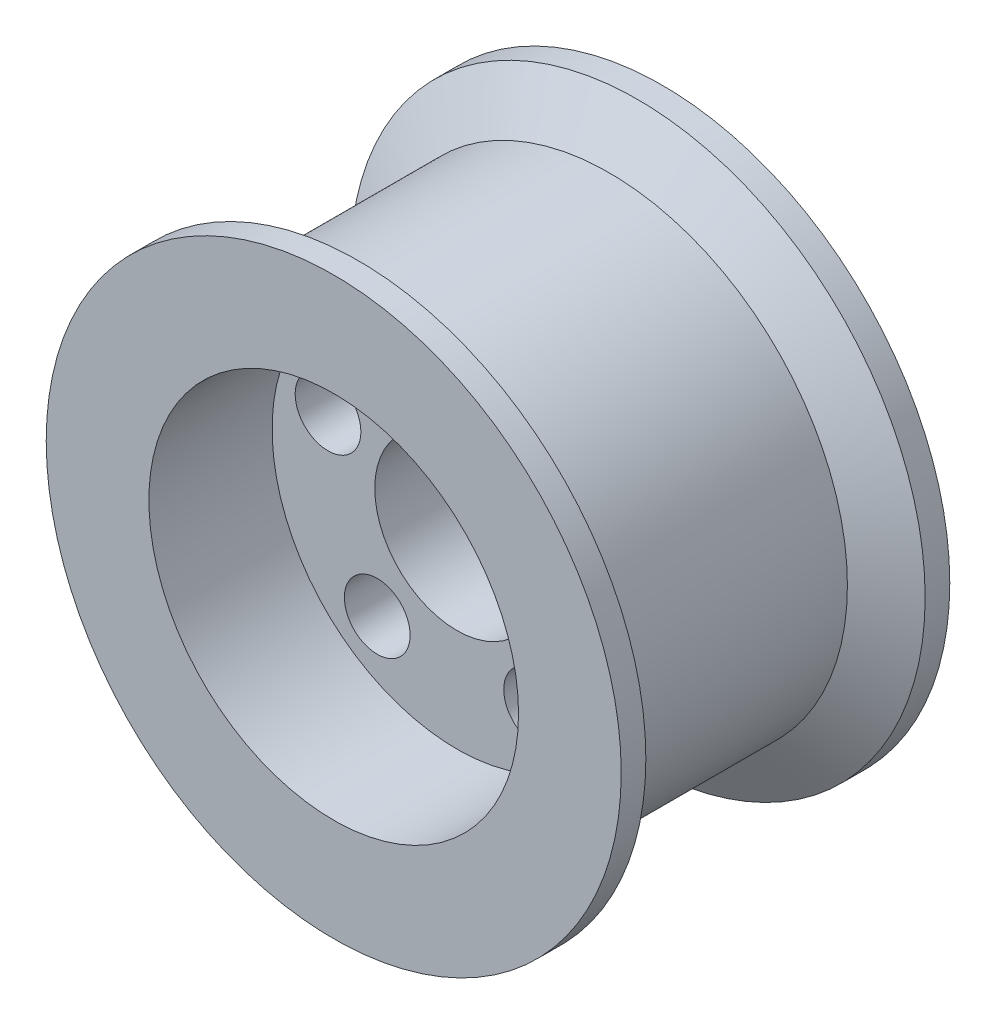
SolidWorks part; units mm, degrees
ref_plane "Plan de face" through (0, 0, 0) normal (0, 0, 1) x (1, 0, 0)
ref_plane "Plan de dessus" through (0, 0, 0) normal (0, 1, 0) x (1, 0, 0)
ref_plane "Plan de droite" through (0, 0, 0) normal (1, 0, 0) x (0, 0, -1)
sketch "Esquisse1" plane through (0, 0, 0) normal (0, 0, 1) x (1, 0, 0)
  circle A0 centre (0, 0) radius 35
  circle A1 centre (0, 0) radius 10
  dimension "D1" = 70
  dimension "D2" = 20
extrude "Boss.-Extru.1" add sketch "Esquisse1" along normal mid plane 40
sketch "Esquisse2" plane through (0, 0, 20) normal (0, 0, 1) x (1, 0, 0)
  circle A0 centre (0, 0) radius 22.5
  dimension "D1" = 45
extrude "Enlèv. mat.-Extru.1" cut sketch "Esquisse2" against normal blind 15
mirror "Symétrie1" about plane through (0, 0, 0) normal (0, 0, 1) of "Enlèv. mat.-Extru.1"
sketch "Esquisse3" plane through (0, 0, 5) normal (0, 0, 1) x (1, 0, 0)
  circle A0 centre (0, 16.5) radius 4
  dimension "D1" = 8
  dimension "D2" = 16.5
extrude "Enlèv. mat.-Extru.2" cut sketch "Esquisse3" against normal through all
pattern_circular "Répétition circulaire1" count 5 over 360 about axis through (0, 0, 0) along (0, 0, 1) of "Enlèv. mat.-Extru.2"
sketch "Esquisse4" plane through (0, 0, 0) normal (0, 1, 0) x (1, 0, 0)
  line L0 (0, 37.9269) -> (0, 0) construction
  line L1 (35, 17) -> (29, 13.5359)
  line L2 (35, -20) -> (35, 20) construction
  line L3 (29, 13.5359) -> (29, -13.5359)
  line L4 (29, -13.5359) -> (35, -17)
  line L5 (35, -17) -> (35, 17)
  dimension "D1" = 60
  dimension "D2" = 60
  dimension "D3" = 6
  dimension "D4" = 3
  dimension "D5" = 3
revolve "Enlèvement de matière-Révolution1" cut sketch "Esquisse4" angle 360 about L0
sketch "Esquisse10" plane through (0, 0, 5) normal (0, 0, 1) x (1, 0, 0)
  circle A0 centre (0, 0) radius 10 construction
  circle A1 centre (0, 0) radius 10
